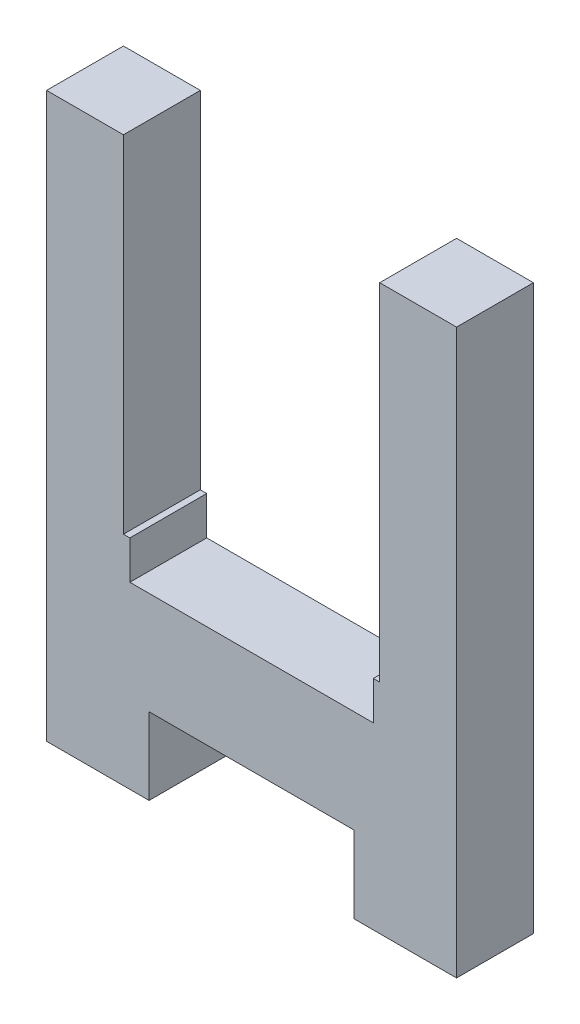
SolidWorks part; units mm, degrees
ref_plane "Plan de face" through (0, 0, 0) normal (0, 0, 1) x (1, 0, 0)
ref_plane "Plan de dessus" through (0, 0, 0) normal (0, 1, 0) x (1, 0, 0)
ref_plane "Plan de droite" through (0, 0, 0) normal (1, 0, 0) x (0, 0, -1)
sketch "Esquisse1" plane through (0, 0, 0) normal (0, 0, 1) x (1, 0, 0)
  line L0 (0, 0) -> (0, 44)
  line L1 (0, 44) -> (-6, 44)
  line L2 (-6, 44) -> (-6, 17)
  line L3 (-6, 17) -> (-6.5, 17)
  line L4 (-6.5, 17) -> (-6.5, 14)
  line L5 (-6.5, 14) -> (-25.5, 14)
  line L6 (-25.5, 14) -> (-25.5, 17)
  line L7 (-25.5, 17) -> (-26, 17)
  line L8 (-26, 17) -> (-26, 44)
  line L9 (-26, 44) -> (-32, 44)
  line L10 (-32, 44) -> (-32, 0)
  line L11 (-32, 0) -> (-24, 0)
  line L12 (-24, 0) -> (-24, 6)
  line L13 (-24, 6) -> (-8, 6)
  line L14 (-8, 6) -> (-8, 0)
  line L15 (-8, 0) -> (0, 0)
  dimension "D1" = 20
  dimension "D2" = 19
  dimension "D3" = 6
  dimension "D4" = 30
  dimension "D5" = 8
  dimension "D6" = 6
  dimension "D7" = 3
  dimension "D8" = 8
extrude "Boss.-Extru.1" add sketch "Esquisse1" along normal blind 6
